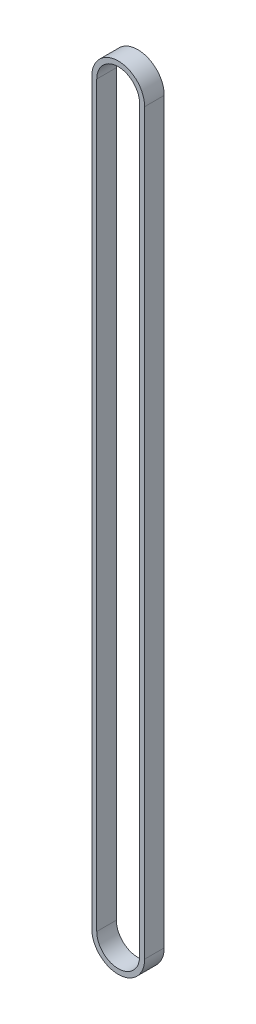
SolidWorks part; units mm, degrees
material "NEOPRENE"
ref_plane "Front Plane" through (0, 0, 0) normal (0, 0, 1) x (1, 0, 0)
ref_plane "Top Plane" through (0, 0, 0) normal (0, 1, 0) x (1, 0, 0)
ref_plane "Right Plane" through (0, 0, 0) normal (1, 0, 0) x (0, 0, -1)
ref_plane "Plane1" through (0, 0, -220.55) normal (0, 0, -1) x (-1, 0, 0)
sketch "Sketch1" plane through (0, 0, -220.55) normal (0, 0, -1) x (-1, 0, 0)
  line L0 (193.675, 78.3) -> (193.675, 643.314) construction
  line L1 (175.175, 78.3) -> (175.175, 643.314) construction
  line L2 (212.175, 78.3) -> (212.175, 643.314) construction
  line L3 (173.4478, 78.3) -> (173.4478, 643.314)
  line L4 (213.9022, 78.3) -> (213.9022, 643.314)
  line L5 (177.2578, 78.3) -> (177.2578, 643.314)
  line L6 (210.0922, 78.3) -> (210.0922, 643.314)
  arc A0 (175.175, 78.3) -> (212.175, 78.3) centre (193.675, 78.3) ccw construction
  arc A2 (212.175, 643.314) -> (175.175, 643.314) centre (193.675, 643.314) ccw construction
  arc A10 (204.6011, 658.2428) -> (201.1407, 660.2407) centre (193.675, 643.314) ccw construction
  arc A11 (204.6011, 658.2428) -> (201.1407, 660.2407) centre (193.675, 643.314) ccw construction
  arc A12 (200.3649, 95.548) -> (196.5054, 96.5822) centre (193.675, 78.3) ccw construction
  arc A13 (200.3649, 95.548) -> (196.5054, 96.5822) centre (193.675, 78.3) ccw
  arc A14 (213.9022, 643.314) -> (173.4478, 643.314) centre (193.675, 643.314) ccw
  arc A15 (173.4478, 78.3) -> (213.9022, 78.3) centre (193.675, 78.3) ccw
  arc A16 (210.0922, 643.314) -> (177.2578, 643.314) centre (193.675, 643.314) ccw
  arc A17 (177.2578, 78.3) -> (210.0922, 78.3) centre (193.675, 78.3) ccw
  point P6 (193.675, 360.807)
  dimension "D1" = 2.0828
  dimension "D2" = 3.81
extrude "Boss-Extrude1" add sketch "Sketch1" along normal mid plane 15
